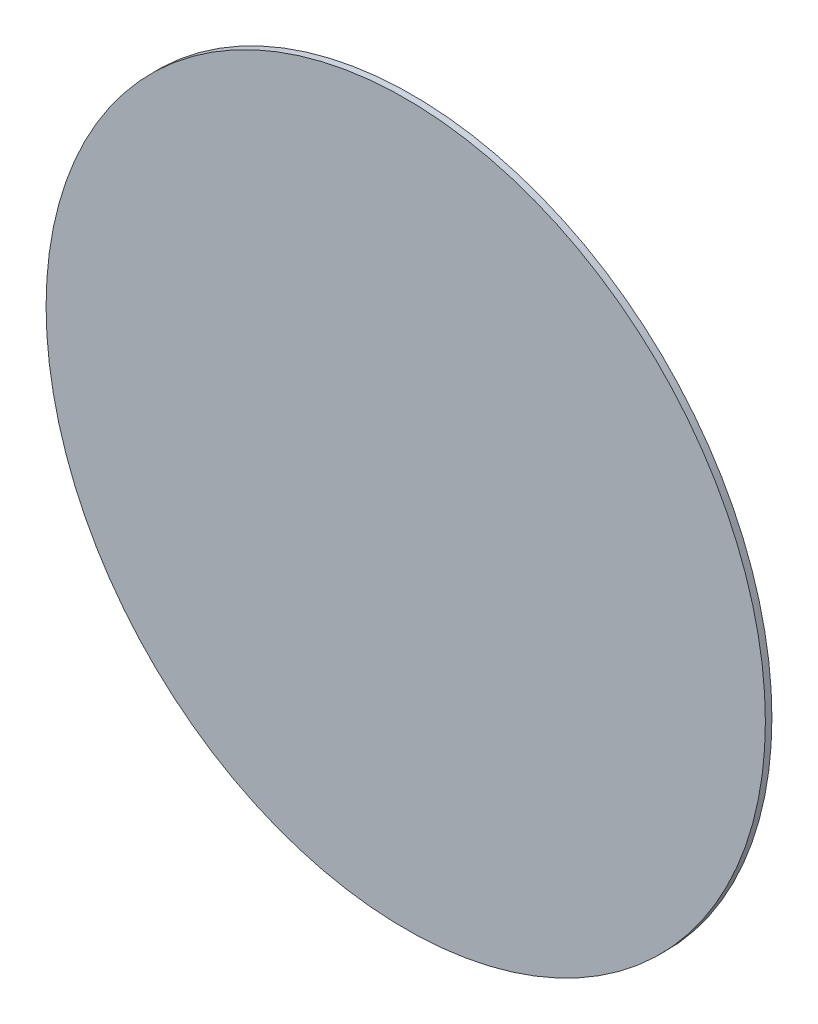
SolidWorks part; units mm, degrees
ref_plane "Спереди" through (0, 0, 0) normal (0, 0, 1) x (1, 0, 0)
ref_plane "Сверху" through (0, 0, 0) normal (0, 1, 0) x (1, 0, 0)
ref_plane "Справа" through (0, 0, 0) normal (1, 0, 0) x (0, 0, -1)
sketch "Эскиз1" plane through (0, 0, 0) normal (0, 0, 1) x (1, 0, 0)
  line L1 (0, 0) -> (500, 0)
  line L2 (0, 0) -> (0, 1300)
  line L3 (0, 1300) -> (500, 1300)
  line L4 (500, 0) -> (500, 1300)
  dimension "D1" = 500
  dimension "D2" = 1300
extrude "Бобышка-Вытянуть1" [suppressed] add sketch "Эскиз1" along normal blind 10 contours L2 L1 L4 L3
sketch "Эскиз2" plane through (0, 0, 0) normal (0, 0, 1) x (1, 0, 0)
  circle A0 centre (0, 0) radius 550
  dimension "D1" = 1100
extrude "Бобышка-Вытянуть2" add sketch "Эскиз2" along normal blind 10
